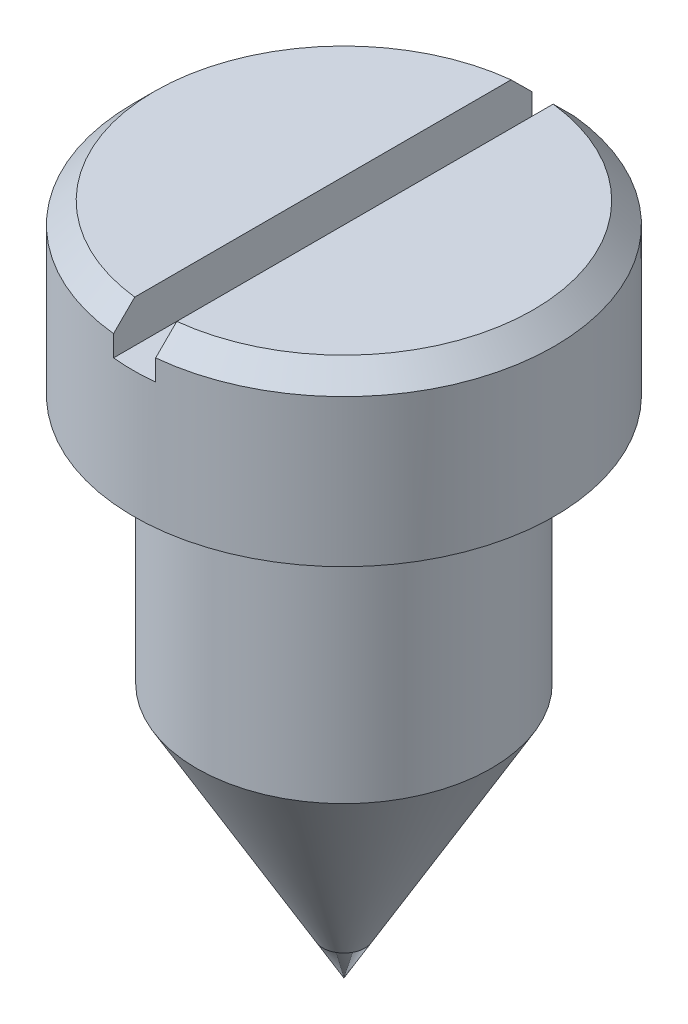
SolidWorks part; units mm, degrees
ref_plane "Front Plane" through (0, 0, 0) normal (0, 0, 1) x (1, 0, 0)
ref_plane "Top Plane" through (0, 0, 0) normal (0, 1, 0) x (1, 0, 0)
ref_plane "Right Plane" through (0, 0, 0) normal (1, 0, 0) x (0, 0, -1)
sketch "Sketch1" plane through (0, 0, 0) normal (0, 0, 1) x (1, 0, 0)
  line L0 (0, 0) -> (3.5, 6.0622)
  line L1 (3.5, 6.0622) -> (3.5, 12)
  line L8 (0, 16) -> (0, 0)
  line L10 (3.5, 12) -> (5, 12)
  line L11 (5, 12) -> (5, 16)
  line L12 (5, 16) -> (0, 16)
  point P5 (3.5, 12)
  dimension "D1" = 30
  dimension "D3" = 5
  dimension "D4" = 3.5
  dimension "D5" = 4
  dimension "D6" = 16
revolve "Revolve1" add sketch "Sketch1" angle 360 about L8
chamfer "Chamfer1" distance 0.5 angle 45 2 edges at (-3.5, 12, 0) (-5, 16, 0)
sketch "Sketch2" plane through (0, 0, 0) normal (0, 0, 1) x (1, 0, 0)
  line L0 (4.5, 16) -> (-4.5, 16) construction
  line L1 (-0.5, 17) -> (0.5, 17)
  line L2 (-0.5, 17) -> (-0.5, 15)
  line L3 (-0.5, 15) -> (0.5, 15)
  line L4 (0.5, 17) -> (0.5, 15)
  line L5 (-0.5, 17) -> (0.5, 15) construction
  line L6 (-0.5, 15) -> (0.5, 17) construction
  point P0 (0, 16)
  dimension "D1" = 1
  dimension "D2" = 2
extrude "Cut-Extrude1" cut sketch "Sketch2" against normal mid plane 10
